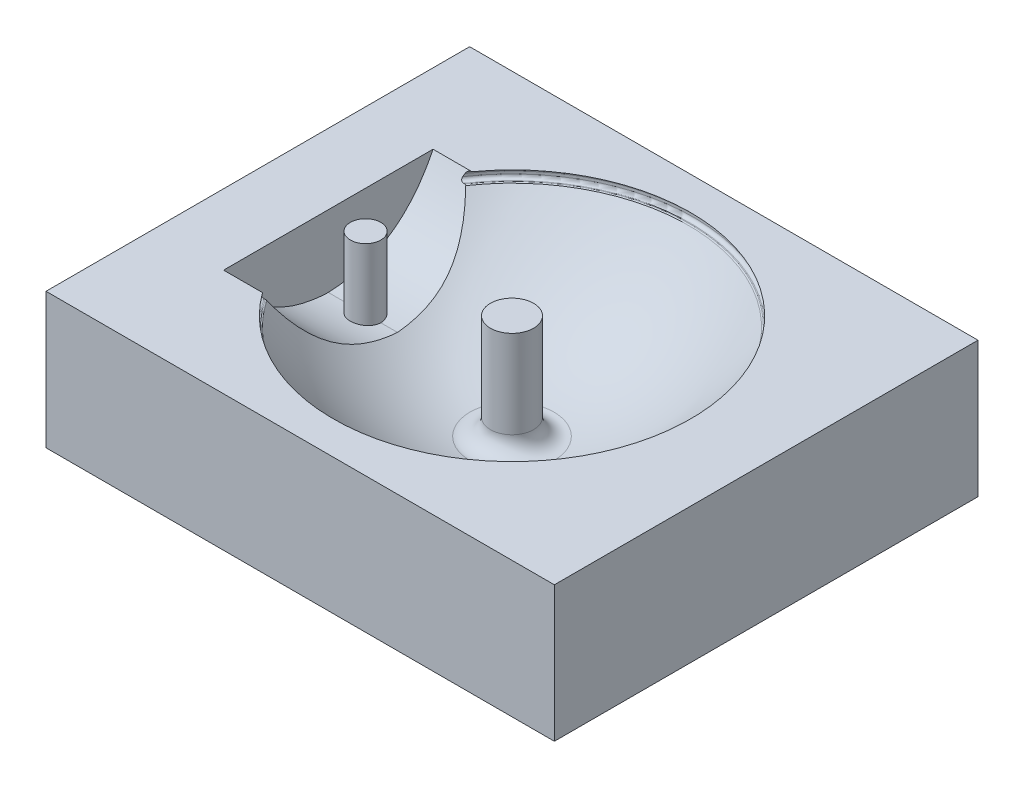
SolidWorks part; units mm, degrees
ref_plane "Front Plane" through (0, 0, 0) normal (0, 0, 1) x (1, 0, 0)
ref_plane "Top Plane" through (0, 0, 0) normal (0, 1, 0) x (1, 0, 0)
ref_plane "Right Plane" through (0, 0, 0) normal (1, 0, 0) x (0, 0, -1)
sketch "Sketch1" plane through (0, 0, 0) normal (0, 0, 1) x (1, 0, 0)
  line L0 (-9.7288, 0) -> (0, 0) construction
  line L1 (0, 0) -> (0, -38.3657) construction
  line L2 (0, 0) -> (86.4, 0) construction
  line L3 (86.4, 0) -> (86.4, -92.4981) construction
  line L4 (0, -2.75) -> (0, 0)
  line L5 (0, 0) -> (-19.04, 0)
  line L6 (-21.04, -2) -> (-21.04, -3.5)
  line L7 (-19.04, -5.5) -> (-18.5148, -5.5)
  line L9 (86.4, -51.52) -> (86.4, -63.74)
  line L10 (0, 0) -> (86.4, 0)
  line L11 (86.4, 0) -> (86.4, -51.52)
  arc A0 (-19.04, 0) -> (-21.04, -2) centre (-19.04, -2) ccw
  arc A1 (-21.04, -3.5) -> (-19.04, -5.5) centre (-19.04, -3.5) ccw
  arc A2 (-18.5148, -5.5) -> (-17.7404, -5.8673) centre (-18.5148, -6.5) cw
  spline S0 degree 3 poles (0, -2.75) (26.4713, -40.6234) (56.7865, -59.0479) (86.4, -51.52) knots 0 0 0 0 0.721199 0.721199 0.721199 0.721199
  spline S1 degree 2 poles (-17.7404, -5.8673) (28.1317, -65.5953) (86.4, -63.74) knots 0 0 0 0.824732 0.824732 0.824732
  point P13 (-21.04, 0)
  point P17 (-21.04, -5.5)
  dimension "D8" = 2
  dimension "D4" = 1
  dimension "D1" = 2.75
  dimension "D2" = 21.04
  dimension "D3" = 5.5
  dimension "D5" = 86.4
  dimension "D6" = 12.22
  dimension "D7" = 63.74
revolve "Revolve1" add sketch "Sketch1" angle 360 about L3
ref_plane "Plane1" through (20, 0, 0) normal (1, 0, 0) x (0, 0, -1)
sketch "Sketch3" plane through (20, 0, 0) normal (1, 0, 0) x (0, 0, -1)
  line L0 (0, 0) -> (0, -63.74) construction
  line L3 (86.4, 0) -> (-86.4, 0) construction
  line L4 (-61.8, 0) -> (61.8, 0)
  spline S0 degree 2 poles (61.8, 0) (41.9944, -40.763) (0, -42.3076) knots 0 0 0 1 1 1
  spline S1 degree 2 poles (-61.8, 0) (-41.9944, -40.763) (0, -42.3076) knots 0 0 0 1 1 1
  dimension "D1" = 123.6
  dimension "D2" = 42.3076
extrude "Boss-Extrude1" add sketch "Sketch3" against normal blind 42
sketch "Sketch4" plane through (0, 0, 0) normal (0, 1, 0) x (1, 0, 0)
  circle A0 centre (86.4, 0) radius 12.745
  dimension "D1" = 25.49
  dimension "D2" = 86.4
extrude "Cut-Extrude2" cut sketch "Sketch4" against normal through all contours A0
sketch "Sketch7" plane through (0, 0, 0) normal (0, 1, 0) x (1, 0, 0)
  circle A0 centre (0, 0) radius 9
  dimension "D1" = 18
extrude "Cut-Extrude4" cut sketch "Sketch7" against normal through all
sketch "Sketch8" plane through (0, 0, 0) normal (0, 1, 0) x (1, 0, 0)
  line L1 (-63.6, 125) -> (236.4, 125)
  line L2 (-63.6, 125) -> (-63.6, -125)
  line L3 (-63.6, -125) -> (236.4, -125)
  line L4 (236.4, 125) -> (236.4, -125)
  line L5 (-63.6, 125) -> (236.4, -125) construction
  line L6 (-63.6, -125) -> (236.4, 125) construction
  point P0 (86.4, 0)
  dimension "D1" = 250
  dimension "D2" = 300
extrude "Boss-Extrude2" add sketch "Sketch8" along normal blind 20 and the other way blind 60 from offset 20 separate body offset against normal yes
combine bodies "Combine1" operation type subtract main body 129 bodies to subtract 111
fillet "Fillet1" radius 10 1 edges at (73.655, -63.3964, 0)
